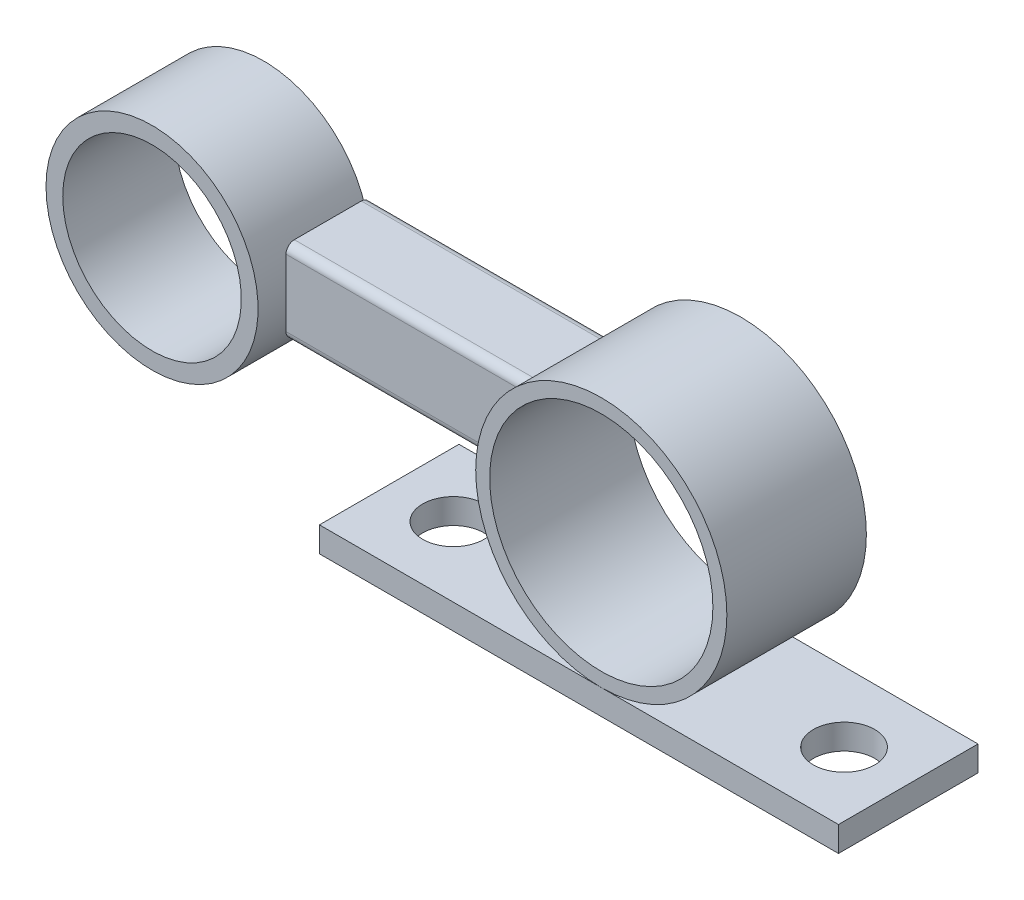
SolidWorks part; units mm, degrees
ref_plane "Спереди" through (0, 0, 0) normal (0, 0, 1) x (1, 0, 0)
ref_plane "Сверху" through (0, 0, 0) normal (0, 1, 0) x (1, 0, 0)
ref_plane "Справа" through (0, 0, 0) normal (1, 0, 0) x (0, 0, -1)
sketch "Эскиз1" plane through (0, 0, 0) normal (0, 1, 0) x (1, 0, 0)
  line L0 (0, 0) -> (0, 20.8351) construction
  line L1 (-46.5, -12.5) -> (46.5, -12.5)
  line L2 (-46.5, -12.5) -> (-46.5, 12.5)
  line L3 (-46.5, 12.5) -> (46.5, 12.5)
  line L4 (46.5, -12.5) -> (46.5, 12.5)
  line L5 (-46.5, -12.5) -> (46.5, 12.5) construction
  line L6 (-46.5, 12.5) -> (46.5, -12.5) construction
  circle A4 centre (35, 0) radius 5.5
  circle A5 centre (-35, 0) radius 5.5
  point P0 (0, 0)
  dimension "D3" = 70
  dimension "D6" = 11
  dimension "D1" = 93
  dimension "D2" = 25
extrude "Бобышка-Вытянуть1" add sketch "Эскиз1" along normal blind 4.5
sketch "Эскиз2" plane through (0, 0, 12.5) normal (0, 0, 1) x (1, 0, 0)
  line L0 (-46.5, 4.5) -> (46.5, 4.5) construction
  line L1 (46.5, 4.5) -> (46.5, 0) construction
  circle A0 centre (4, 27) radius 22.5
  circle A1 centre (4, 27) radius 20
  dimension "D1" = 45
  dimension "D2" = 40
  dimension "D3" = 65
extrude "Бобышка-Вытянуть2" add sketch "Эскиз2" against normal blind 25 separate body
ref_plane "Плоскость4" through (0, 0, -5) normal (0, 0, -1) x (-1, 0, 0)
sketch "Эскиз3" plane through (0, 0, -5) normal (0, 0, 1) x (1, 0, 0)
  line L0 (-62.4944, 27.5) -> (-18.4944, 27.5)
  line L1 (-46.5, 0) -> (46.5, 0) construction
  circle A0 centre (4, 27) radius 22.5 construction
  dimension "D1" = 27.5
  dimension "D2" = 44
other "Труба bxbxs гост8639-82 15 X 15 X 1(1)"
ref_plane "Плоскость3" through (-62.4944, 27.5, -5) normal (1, 0, 0) x (0, -1, 0)
sketch "Sketch1" plane through (-62.4944, 27.5, -5) normal (1, 0, 0) x (0, -1, 0)
  line L0 (-6, -6.5) -> (6, -6.5)
  line L1 (-6.5, -6) -> (-6.5, 6)
  line L2 (6, 6.5) -> (-6, 6.5)
  line L3 (6.5, 6) -> (6.5, -6)
  line L4 (-6, -7.5) -> (6, -7.5)
  line L5 (-7.5, -6) -> (-7.5, 6)
  line L6 (6, 7.5) -> (-6, 7.5)
  line L7 (7.5, 6) -> (7.5, -6)
  arc A0 (7.5, 6) -> (6, 7.5) centre (6, 6) ccw
  arc A1 (6, -7.5) -> (7.5, -6) centre (6, -6) ccw
  arc A2 (-7.5, -6) -> (-6, -7.5) centre (-6, -6) ccw
  arc A3 (-6, 7.5) -> (-7.5, 6) centre (-6, 6) ccw
  arc A4 (-6, 6.5) -> (-6.5, 6) centre (-6, 6) ccw
  arc A5 (6.5, 6) -> (6, 6.5) centre (6, 6) ccw
  arc A6 (6, -6.5) -> (6.5, -6) centre (6, -6) ccw
  arc A7 (-6.5, -6) -> (-6, -6.5) centre (-6, -6) ccw
  point P0 (-7.5, 0)
  point P1 (7.5, 0)
  point P2 (0, 7.5)
  point P3 (0, -7.5)
  point P4 (0, 0)
  point P5 (-7.5, -7.5)
  point P6 (7.5, -7.5)
  point P7 (7.5, 7.5)
  point P8 (-7.5, 7.5)
  point P33 (0, 0)
  dimension "D1" = 1.5
  dimension "Thickness" = 1
  dimension "V_leg" = 15
sketch "Эскиз7" plane through (0, 0, -12.5) normal (0, 0, -1) x (-1, 0, 0)
  line L0 (62.4944, 21.5) -> (62.4944, 33.5) construction
  circle A0 centre (81.4944, 27.5) radius 16
  circle A1 centre (81.4944, 27.5) radius 19
  dimension "D1" = 38
  dimension "D2" = 32
extrude "Бобышка-Вытянуть3" add sketch "Эскиз7" against normal blind 20 separate body
